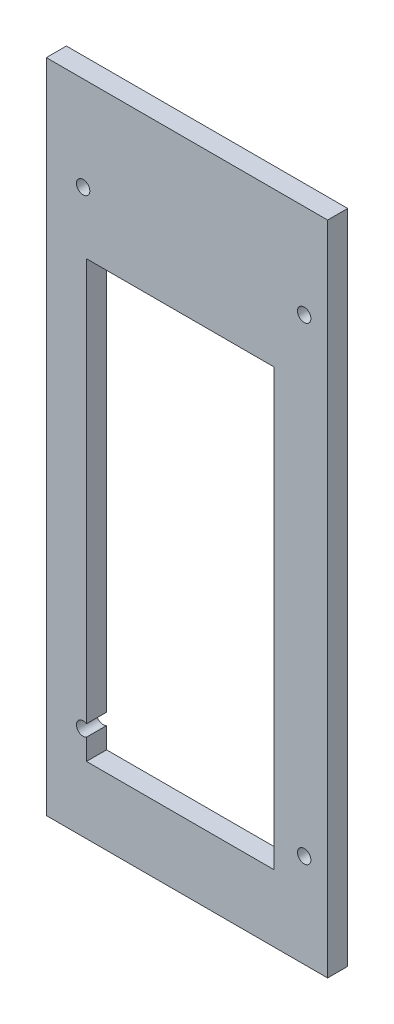
SolidWorks part; units mm, degrees
ref_plane "Front Plane" through (0, 0, 0) normal (0, 0, 1) x (1, 0, 0)
ref_plane "Top Plane" through (0, 0, 0) normal (0, 1, 0) x (1, 0, 0)
ref_plane "Right Plane" through (0, 0, 0) normal (1, 0, 0) x (0, 0, -1)
sketch "Sketch1" plane through (0, 0, 0) normal (0, 0, 1) x (1, 0, 0)
  line L0 (21, -82.0031) -> (21, -17.0031) construction
  line L2 (0, 0) -> (0, -114.0061)
  line L4 (42, 0) -> (42, -114.0061)
  line L5 (36, -8.0031) -> (42, -8.0031)
  line L6 (0, 0) -> (0, 18.809) construction
  line L7 (42, -8.0031) -> (42, -22.0031)
  line L8 (0, -22.0031) -> (0, 0)
  line L9 (6, -106.0031) -> (36, -106.0031)
  line L10 (0, -22.0031) -> (0, 0)
  line L11 (0, -8.0031) -> (0, -22.0031)
  line L12 (42, -22.0031) -> (42, 0)
  line L13 (6, -8.0031) -> (0, -8.0031)
  line L14 (42, -22.0031) -> (42, 0)
  line L15 (6, -106.0031) -> (36, -106.0031)
  line L16 (36, -31.0031) -> (6, -31.0031)
  line L17 (6, -31.0031) -> (6, -96.0031)
  line L18 (6, -96.0031) -> (36, -96.0031)
  line L19 (36, -31.0031) -> (36, -96.0031)
  line L20 (0, -57.0031) -> (42, -57.0031) construction
  line L21 (6, -106.0031) -> (0, -106.0031)
  line L22 (4, -92.0031) -> (4, -89.5031) construction
  line L23 (0, -106.0031) -> (0, -92.0031)
  line L24 (42, -92.0031) -> (42, -114.0061)
  line L25 (42, -106.0031) -> (42, -92.0031)
  line L26 (42, -92.0031) -> (42, -114.0061)
  line L27 (0, -92.0031) -> (0, -114.0061)
  line L28 (36, -106.0031) -> (42, -106.0031)
  line L29 (0, -92.0031) -> (0, -114.0061)
  line L31 (6, -8.0031) -> (36, -8.0031)
  point P25 (21, -96.0031)
  point P26 (21, -31.0031)
  dimension "D2" = 39
  dimension "D3" = 30
  dimension "D1" = 6
  dimension "D5" = 26
  dimension "D6" = 6
  dimension "D7" = 10
extrude "Boss-Extrude1" add sketch "Sketch1" along normal blind 3
sketch "Sketch3" plane through (0, 0, 0) normal (0, 0, -1) x (-1, 0, 0)
  line L2 (-42, -8.0031) -> (-42, -106.0031) construction
  line L7 (-42, -57.0031) -> (0, -57.0031) construction
  line L8 (0, -8.0031) -> (0, -106.0031) construction
  line L10 (-18, -84.0031) -> (-18, -96.0031) construction
  circle A0 centre (-38.5, -22.0031) radius 1
  circle A1 centre (-5.5, -22.0031) radius 1
  circle A2 centre (-5.5, -92.0031) radius 1
  circle A3 centre (-38.5, -92.0031) radius 1
  dimension "D1" = 2
  dimension "D4" = 70
  dimension "D5" = 2
  dimension "D6" = 70
  dimension "D2" = 33
  dimension "D3" = 3.5
extrude "Cut-Extrude1" cut sketch "Sketch3" against normal up to surface (3 mm away) up to face at (21, -57.0031, 3)
sketch "Sketch4" plane through (0, 0, 3) normal (0, 0, 1) x (1, 0, 0)
  line L0 (6, -96.0031) -> (36, -96.0031) construction
  line L1 (36, -31.0031) -> (34, -31.0031)
  line L2 (36, -31.0031) -> (36, -96.0031)
  line L3 (36, -96.0031) -> (34, -96.0031)
  line L4 (34, -31.0031) -> (34, -96.0031)
  dimension "D1" = 2
extrude "Boss-Extrude2" add sketch "Sketch4" against normal up to surface (3 mm away) up to face at (39.5, -92.0031, 0)
